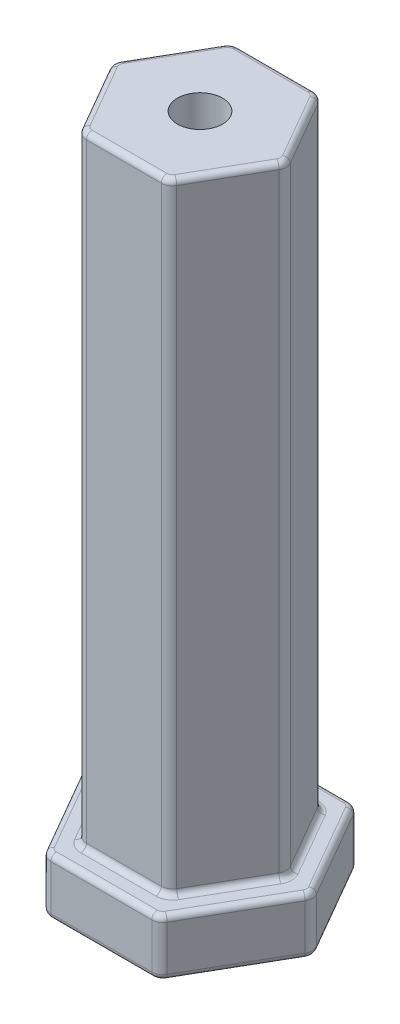
SolidWorks part; units mm, degrees
ref_plane "Front Plane" through (0, 0, 0) normal (0, 0, 1) x (1, 0, 0)
ref_plane "Top Plane" through (0, 0, 0) normal (0, 1, 0) x (1, 0, 0)
ref_plane "Right Plane" through (0, 0, 0) normal (1, 0, 0) x (0, 0, -1)
sketch "Sketch1" plane through (0, 0, 0) normal (0, 1, 0) x (1, 0, 0)
  line L1 (3.8971, -6.75) -> (7.7942, 0)
  line L2 (7.7942, 0) -> (3.8971, 6.75)
  line L3 (3.8971, 6.75) -> (-3.8971, 6.75)
  line L4 (-3.8971, 6.75) -> (-7.7942, 0)
  line L5 (-7.7942, 0) -> (-3.8971, -6.75)
  line L6 (-3.8971, -6.75) -> (3.8971, -6.75)
  circle A0 centre (0, 0) radius 6.75 construction
  dimension "D1" = 13.5
extrude "Boss-Extrude1" add sketch "Sketch1" along normal blind 55
sketch "Sketch2" plane through (0, 0, 0) normal (0, -1, 0) x (1, 0, 0)
  line L1 (5.0518, -8.75) -> (10.1036, 0)
  line L2 (10.1036, 0) -> (5.0518, 8.75)
  line L3 (5.0518, 8.75) -> (-5.0518, 8.75)
  line L4 (-5.0518, 8.75) -> (-10.1036, 0)
  line L5 (-10.1036, 0) -> (-5.0518, -8.75)
  line L6 (-5.0518, -8.75) -> (5.0518, -8.75)
  circle A0 centre (0, 0) radius 8.75 construction
  dimension "D1" = 17.5
extrude "Boss-Extrude2" add sketch "Sketch2" along normal blind 5
sketch "Sketch5" plane through (0, 55, 0) normal (0, 1, 0) x (1, 0, 0)
  point P0 (0, 0)
hole_wizard "Ø4.0mm Dowel Hole1" positions "Sketch5" profile "Sketch6" hole size "Ø4.0" standard "ISO"
sketch "Sketch6" plane through (0, 55, 0) normal (1, 0, 0) x (0, 0, 1)
  line L0 (0, 0) -> (0, 21.2017)
  line L1 (0, 21.2017) -> (2, 20)
  line L2 (2, 20) -> (2, 0)
  line L5 (2, 0) -> (0, 0)
  line L10 (0, 21.2017) -> (-2, 20) construction
  line L11 (0, -6.35) -> (0, 107.95) construction
  dimension "Hole Dia." = 4
  dimension "Hole Depth" = 20
  dimension "Drill Angle" = 118
fillet "Fillet3" radius 1 6 edges at (-3.8971, 27.5, -6.75) (3.8971, 27.5, -6.75) (7.7942, 27.5, 0) (3.8971, 27.5, 6.75) (-3.8971, 27.5, 6.75) (-7.7942, 27.5, 0)
fillet "Fillet4" radius 1 6 edges at (5.0518, -2.5, -8.75) (10.1036, -2.5, 0) (5.0518, -2.5, 8.75) (-5.0518, -2.5, 8.75) (-10.1036, -2.5, 0) (-5.0518, -2.5, -8.75)
fillet "Fillet5" radius 0.5 36 edges at (7.6395, 0, 0) (5.8457, 0, 3.375) (3.8198, 0, 6.616) (0, 0, 6.75) (-3.8198, 0, 6.616) (-5.8457, 0, 3.375) (-7.6395, 0, 0) (-5.8457, 0, -3.375) (-3.8198, 0, -6.616) (0, 0, -6.75) (3.8198, 0, -6.616) (4.9745, 0, -8.616) (0, 0, -8.75) (-4.9745, 0, -8.616) (-7.5777, 0, -4.375) (-9.9489, 0, 0) (-7.5777, 0, 4.375) (-4.9745, 0, 8.616) (0, 0, 8.75) (4.9745, 0, 8.616) (7.5777, 0, 4.375) (9.9489, 0, 0) (9.9489, -5, 0) (7.5777, -5, -4.375) (4.9745, -5, -8.616) (0, -5, -8.75) (-4.9745, -5, -8.616) (-7.5777, -5, -4.375) (-9.9489, -5, 0) (-7.5777, -5, 4.375) (-4.9745, -5, 8.616) (0, -5, 8.75) (4.9745, -5, 8.616) (5.8457, 0, -3.375) (7.5777, 0, -4.375) (7.5777, -5, 4.375)
fillet "Fillet6" radius 0.5 12 edges at (7.6395, 55, 0) (5.8457, 55, 3.375) (3.8198, 55, 6.616) (0, 55, 6.75) (-3.8198, 55, 6.616) (-5.8457, 55, 3.375) (-7.6395, 55, 0) (-5.8457, 55, -3.375) (-3.8198, 55, -6.616) (0, 55, -6.75) (3.8198, 55, -6.616) (5.8457, 55, -3.375)
